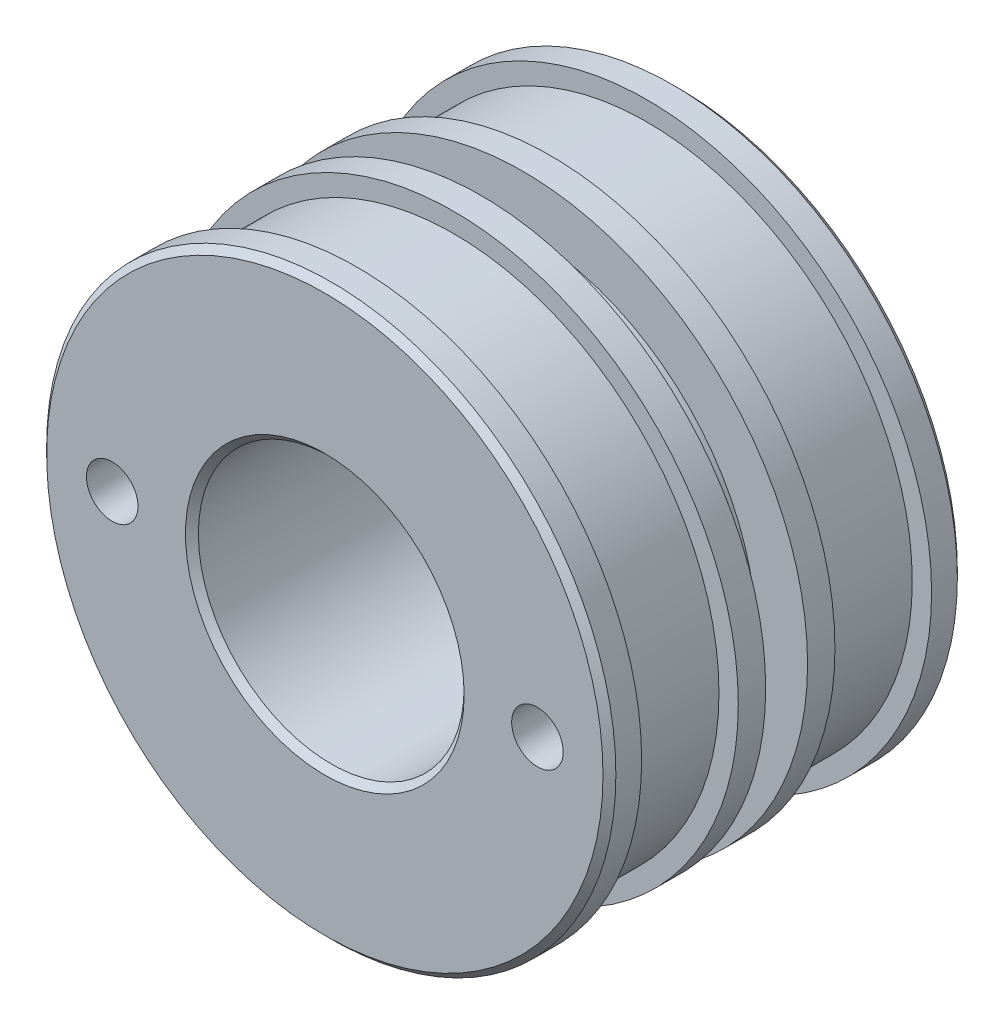
SolidWorks part; units mm, degrees
ref_plane "Front Plane" through (0, 0, 0) normal (0, 0, 1) x (1, 0, 0)
ref_plane "Top Plane" through (0, 0, 0) normal (0, 1, 0) x (1, 0, 0)
ref_plane "Right Plane" through (0, 0, 0) normal (1, 0, 0) x (0, 0, -1)
sketch "Sketch1" plane through (0, 0, 0) normal (0, 0, 1) x (1, 0, 0)
  circle A0 centre (0, 0) radius 44.175
  circle A1 centre (0, 0) radius 20.625
  dimension "D1" = 88.35
  dimension "D2" = 41.25
extrude "Boss-Extrude1" add sketch "Sketch1" against normal blind 55
sketch "Sketch2" plane through (0, 0, 0) normal (1, 0, 0) x (0, 0, -1)
  line L0 (0, 0) -> (60.6503, 0) construction
  line L1 (55, 44.175) -> (0, 44.175) construction
  line L2 (5, 44.175) -> (20, 44.175)
  line L3 (5, 44.175) -> (5, 41.175)
  line L4 (5, 41.175) -> (20, 41.175)
  line L5 (20, 44.175) -> (20, 41.175)
  line L6 (5, 44.175) -> (20, 41.175) construction
  line L7 (5, 41.175) -> (20, 44.175) construction
  line L8 (0, 44.175) -> (0, -44.175) construction
  line L9 (24.25, 44.175) -> (30.75, 44.175)
  line L10 (24.25, 44.175) -> (24.25, 36.175)
  line L11 (24.25, 36.175) -> (30.75, 36.175)
  line L12 (30.75, 44.175) -> (30.75, 36.175)
  line L13 (24.25, 44.175) -> (30.75, 36.175) construction
  line L14 (24.25, 36.175) -> (30.75, 44.175) construction
  line L15 (35, 44.175) -> (50, 44.175)
  line L16 (35, 44.175) -> (35, 41.175)
  line L17 (35, 41.175) -> (50, 41.175)
  line L18 (50, 44.175) -> (50, 41.175)
  line L19 (35, 44.175) -> (50, 41.175) construction
  line L20 (35, 41.175) -> (50, 44.175) construction
  line L21 (55, -44.175) -> (55, 44.175) construction
  point P7 (12.5, 42.675)
  point P14 (27.5, 40.175)
  point P19 (42.5, 42.675)
  dimension "D1" = 3
  dimension "D2" = 5
  dimension "D3" = 15
  dimension "D4" = 6.5
  dimension "D5" = 8
  dimension "D6" = 4.25
  dimension "D7" = 5
revolve "Cut-Revolve1" cut sketch "Sketch2" angle 360 about L0
chamfer "Chamfer1" distance 1 angle 45 4 edges at (44.175, 0, 0) (20.625, 0, -55) (20.625, 0, 0) (44.175, 0, -55)
sketch "Sketch3" plane through (0, 0, -55) normal (0, 0, -1) x (-1, 0, 0)
  circle A0 centre (0, 0) radius 24.5
  dimension "D1" = 49
extrude "Cut-Extrude1" cut sketch "Sketch3" against normal blind 15
chamfer "Chamfer2" distance 1 angle 45 1 edges at (-24.5, 0, -55)
sketch "Sketch4" plane through (0, 0, 0) normal (0, 0, 1) x (1, 0, 0)
  line L0 (-33, 0) -> (33, 0) construction
  circle A0 centre (0, 0) radius 33 construction
  circle A1 centre (-33, 0) radius 4
  circle A2 centre (33, 0) radius 4
  dimension "D1" = 66
  dimension "D2" = 8
extrude "Cut-Extrude2" cut sketch "Sketch4" against normal blind 9
